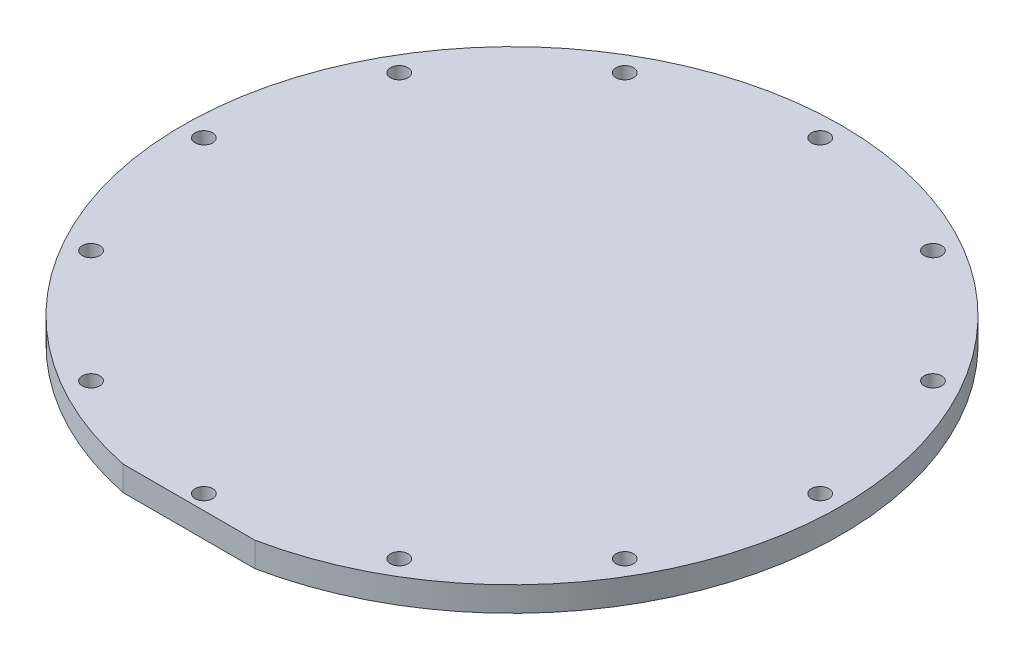
SolidWorks part; units mm, degrees
material "AISI 304"
ref_plane "Front" through (0, 0, 0) normal (0, 0, 1) x (1, 0, 0)
ref_plane "Top" through (0, 0, 0) normal (0, 1, 0) x (1, 0, 0)
ref_plane "Right" through (0, 0, 0) normal (1, 0, 0) x (0, 0, -1)
sketch "Sketch1" plane through (0, 0, 0) normal (0, 0, 1) x (1, 0, 0)
  line L0 (0, 0) -> (0, 9.525)
  line L2 (0, 0) -> (127, 0)
  line L3 (127, 0) -> (127, 9.525)
  line L4 (127, 9.525) -> (0, 9.525)
  dimension "D2" = 127
  dimension "D3" = 9.525
revolve "Revolve1" add sketch "Sketch1" angle 360 about L0
hole_wizard "1/4 Clearance Hole1" positions "Sketch2" profile "Sketch3" hole size "1/4" standard "ANSI Inch" end condition up to next
sketch "Sketch2" plane through (0, 9.525, 0) normal (0, 1, 0) x (1, 0, 0)
  line L0 (0, 0) -> (0, 118.745) construction
  point P0 (0, 118.745)
  point P6 (59.3725, 102.8362)
  point P7 (102.8362, 59.3725)
  point P8 (118.745, 0)
  point P9 (102.8362, -59.3725)
  point P10 (59.3725, -102.8362)
  point P11 (0, -118.745)
  point P12 (-59.3725, -102.8362)
  point P13 (-102.8362, -59.3725)
  point P18 (-118.745, 0)
  point P19 (-102.8362, 59.3725)
  point P20 (-59.3725, 102.8362)
  dimension "D2" = 118.745
  dimension "D1" = 12
sketch "Sketch3" plane through (0, 9.525, -118.745) normal (1, 0, 0) x (0, 0, 1)
  line L0 (0, 0) -> (0, 9.525)
  line L1 (0, 9.525) -> (3.3782, 9.525)
  line L2 (3.3782, 9.525) -> (3.3782, 0)
  line L5 (3.3782, 0) -> (0, 0)
  line L11 (0, -6.35) -> (0, 107.95) construction
  dimension "Thru Hole Dia." = 6.7564
  dimension "Thru Hole Depth" = 9.525
sketch "Sketch4" plane through (0, 9.525, 0) normal (0, 1, 0) x (1, 0, 0)
  line L1 (-25.4, -124.4341) -> (25.4, -124.4341)
  line L2 (-25.4, -124.4341) -> (-25.4, -127)
  line L3 (-25.4, -127) -> (25.4, -127)
  line L4 (25.4, -124.4341) -> (25.4, -127)
  circle A0 centre (0, 0) radius 127 construction
  dimension "D1" = 50.8
extrude "Cut-Extrude1" cut sketch "Sketch4" against normal up to next
